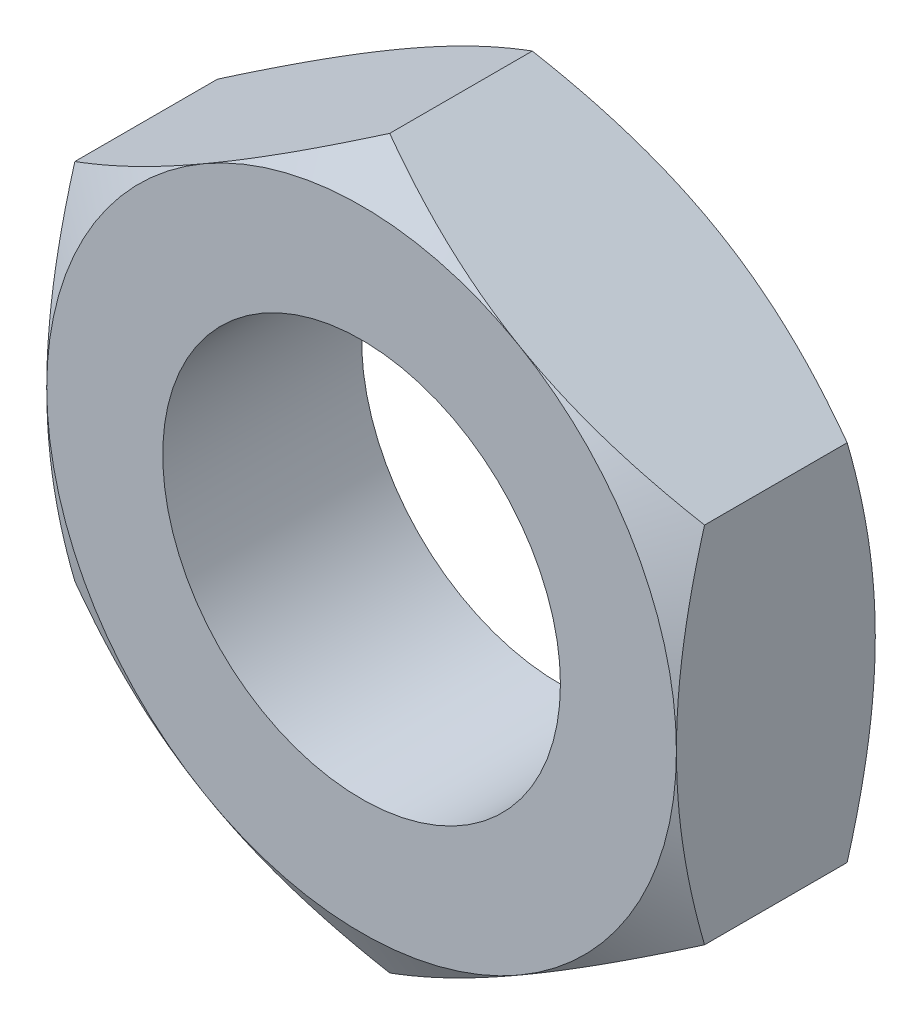
SolidWorks part; units mm, degrees
material "1.4000 (X6Cr13)"
ref_plane "Płaszczyzna przednia" through (0, 0, 0) normal (0, 0, 1) x (1, 0, 0)
ref_plane "Płaszczyzna górna" through (0, 0, 0) normal (0, 1, 0) x (1, 0, 0)
ref_plane "Płaszczyzna prawa" through (0, 0, 0) normal (1, 0, 0) x (0, 0, -1)
sketch "Szkic1" plane through (0, 0, 0) normal (0, 0, 1) x (1, 0, 0)
  line L1 (-9.5, 5.4848) -> (-9.5, -5.4848)
  line L2 (-9.5, -5.4848) -> (0, -10.9697)
  line L3 (0, -10.9697) -> (9.5, -5.4848)
  line L4 (9.5, -5.4848) -> (9.5, 5.4848)
  line L5 (9.5, 5.4848) -> (0, 10.9697)
  line L6 (0, 10.9697) -> (-9.5, 5.4848)
  circle A0 centre (0, 0) radius 6
  circle A1 centre (0, 0) radius 9.5 construction
  dimension "d" = 12
  dimension "s" = 19
extrude "Dodanie-wyciągnięcie1" add sketch "Szkic1" along normal mid plane 6
sketch "Szkic2" plane through (0, 0, 3) normal (0, 0, 1) x (1, 0, 0)
  circle A0 centre (0, 0) radius 9.5
  dimension "D1" = 19
extrude "Wytnij-wyciągnięcie2" cut sketch "Szkic2" against normal blind 6 draft 60 flip side to cut
mirror "Lustro1" about plane through (0, 0, 0) normal (0, 0, 1) of "Wytnij-wyciągnięcie2"
equation "\"D1@Szkic2\" = \"s@Szkic1\""
equation "\"D1@Wytnij-wyciągnięcie2\" = \"m@Dodanie-wyciągnięcie1\""
